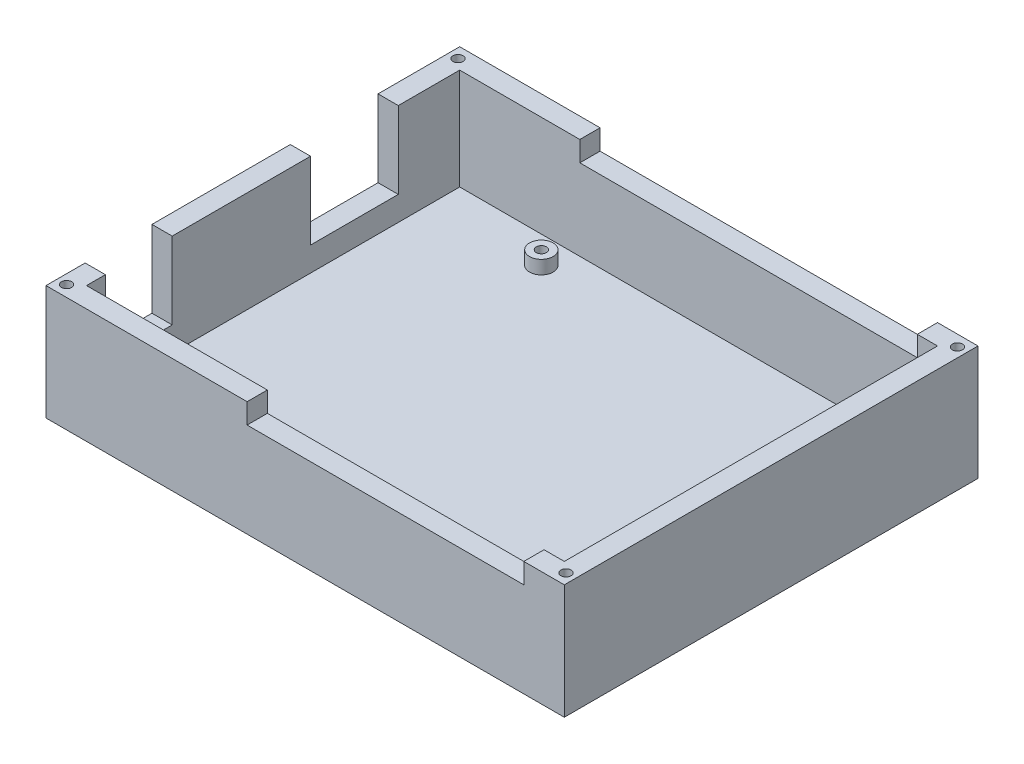
SolidWorks part; units mm, degrees
ref_plane "前基準面" through (0, 0, 0) normal (0, 0, 1) x (1, 0, 0)
ref_plane "上基準面" through (0, 0, 0) normal (0, 1, 0) x (1, 0, 0)
ref_plane "右基準面" through (0, 0, 0) normal (1, 0, 0) x (0, 0, -1)
sketch "Sketch1" plane through (0, 0, 0) normal (0, 1, 0) x (1, 0, 0)
  line L0 (0, 57.3725) -> (0, -53.5143) construction
  line L1 (-38.4, 30.65) -> (-38.4, -30.65)
  line L2 (-38.4, -30.65) -> (38.4, -30.65)
  line L3 (38.4, 30.65) -> (38.4, -30.65)
  line L4 (-38.4, 30.65) -> (38.4, 30.65)
  line L6 (0, -55) -> (0, 55) construction
  line L8 (-58.3013, 0) -> (68.1611, 0) construction
  line L9 (-55, 0) -> (55, 0) construction
  dimension "D1" = 76.8
  dimension "D2" = 61.3
extrude "Boss-Extrude1" add sketch "Sketch1" against normal blind 2
sketch "Sketch2" plane through (0, 0, 0) normal (0, 1, 0) x (1, 0, 0)
  line L0 (-38.4, 30.65) -> (-38.4, -30.65) construction
  line L1 (38.4, 30.65) -> (-38.4, 30.65) construction
  line L2 (38.4, -30.65) -> (38.4, 30.65) construction
  line L3 (-38.4, -30.65) -> (38.4, -30.65) construction
  line L4 (-38.4, 30.65) -> (-38.4, -30.65)
  line L5 (38.4, 30.65) -> (-38.4, 30.65)
  line L6 (38.4, -30.65) -> (38.4, 30.65)
  line L7 (-38.4, -30.65) -> (38.4, -30.65)
  line L8 (-35.4, 27.65) -> (-35.4, -27.65)
  line L9 (-35.4, -27.65) -> (35.4, -27.65)
  line L10 (35.4, -27.65) -> (35.4, 27.65)
  line L11 (35.4, 27.65) -> (-35.4, 27.65)
  dimension "D1" = 3
extrude "Boss-Extrude2" add sketch "Sketch2" along normal blind 15
sketch "Sketch6" plane through (-38.4, 0, 0) normal (-1, 0, 0) x (0, 0, 1)
  line L0 (-18.55, 18.2707) -> (-18.55, 3.6)
  line L1 (-18.55, 3.6) -> (-5.55, 3.6)
  line L2 (-5.55, 3.6) -> (-5.55, 18.2707)
  line L3 (-5.55, 18.2707) -> (-18.55, 18.2707)
  line L4 (-32.2624, 0) -> (35.5151, 0) construction
  line L5 (33.715, 0) -> (-33.715, 0) construction
  line L7 (0, -9.35) -> (0, 9.35) construction
  dimension "D1" = 3.6
  dimension "D2" = 18.55
  dimension "D3" = 13
extrude "Cut-Extrude1" cut sketch "Sketch6" against normal up to next
sketch "Sketch7" plane through (-38.4, 0, 0) normal (-1, 0, 0) x (0, 0, 1)
  line L0 (33.715, 0) -> (-33.715, 0) construction
  line L1 (14.95, 15.3437) -> (24.85, 15.3437)
  line L2 (14.95, 15.3437) -> (14.95, 3.6)
  line L3 (14.95, 3.6) -> (24.85, 3.6)
  line L4 (24.85, 15.3437) -> (24.85, 3.6)
  line L6 (0, -9.35) -> (0, 9.35) construction
  dimension "D1" = 3.6
  dimension "D2" = 24.85
  dimension "D3" = 9.9
extrude "Cut-Extrude2" cut sketch "Sketch7" against normal up to next
sketch "Sketch8" plane through (0, 0, 30.65) normal (0, 0, 1) x (1, 0, 0)
  line L0 (-38.4, 15) -> (38.4, 15) construction
  line L1 (-8.6, 23.4773) -> (32.4, 23.4773)
  line L2 (-8.6, 23.4773) -> (-8.6, 12)
  line L3 (-8.6, 12) -> (32.4, 12)
  line L4 (32.4, 23.4773) -> (32.4, 12)
  line L6 (0, -9.35) -> (0, 9.35) construction
  dimension "D1" = 3
  dimension "D2" = 8.6
  dimension "D3" = 32.4
extrude "Cut-Extrude3" cut sketch "Sketch8" against normal up to next
sketch "Sketch9" plane through (0, 0, -30.65) normal (0, 0, -1) x (-1, 0, 0)
  line L0 (-38.4, 15) -> (38.4, 15) construction
  line L1 (-32.4, 25.6397) -> (17.6, 25.6397)
  line L2 (-32.4, 25.6397) -> (-32.4, 12)
  line L3 (-32.4, 12) -> (17.6, 12)
  line L4 (17.6, 25.6397) -> (17.6, 12)
  line L6 (0, 9.35) -> (0, -9.35) construction
  dimension "D1" = 3
  dimension "D2" = 32.4
  dimension "D3" = 17.6
extrude "Cut-Extrude4" cut sketch "Sketch9" against normal up to next
sketch "Sketch10" plane through (0, 0, 0) normal (0, 1, 0) x (1, 0, 0)
  line L0 (0, -9.35) -> (0, 9.35) construction
  line L1 (-9.35, 0) -> (9.35, 0) construction
  circle A0 centre (-19.3, 23.65) radius 1.75
  circle A1 centre (-20.4, -24.15) radius 1.75
  circle A2 centre (31.5, 8.45) radius 1.75
  circle A3 centre (31.5, -19.45) radius 1.75
  dimension "D1" = 51.9
  dimension "D2" = 50.8
  dimension "D3" = 15.2
  dimension "D4" = 27.9
  dimension "D5" = 4.7
  dimension "D6" = 1.1
  dimension "D7" = 20.4
  dimension "D8" = 24.15
extrude "Boss-Extrude4" add sketch "Sketch10" along normal blind 2
sketch "Sketch11" plane through (0, 2, 0) normal (0, 1, 0) x (1, 0, 0)
  circle A0 centre (-19.3, 23.65) radius 0.75
  circle A1 centre (-20.4, -24.15) radius 0.75
  circle A2 centre (31.5, 8.45) radius 0.75
  circle A3 centre (31.5, -19.45) radius 0.75
extrude "Cut-Extrude5" cut sketch "Sketch11" against normal blind 2.5
sketch "Sketch12" plane through (0, 15, 0) normal (0, 1, 0) x (1, 0, 0)
  line L0 (0, -9.35) -> (0, 9.35) construction
  line L1 (-9.35, 0) -> (9.35, 0) construction
  circle A0 centre (-37, 29) radius 0.75
  circle A1 centre (37, 29) radius 0.75
  circle A2 centre (37, -29) radius 0.75
  circle A3 centre (-37, -29) radius 0.75
  dimension "D1" = 37
  dimension "D2" = 29
  dimension "D7" = 37
  dimension "D8" = 29
extrude "Cut-Extrude6" cut sketch "Sketch12" against normal blind 2.5
